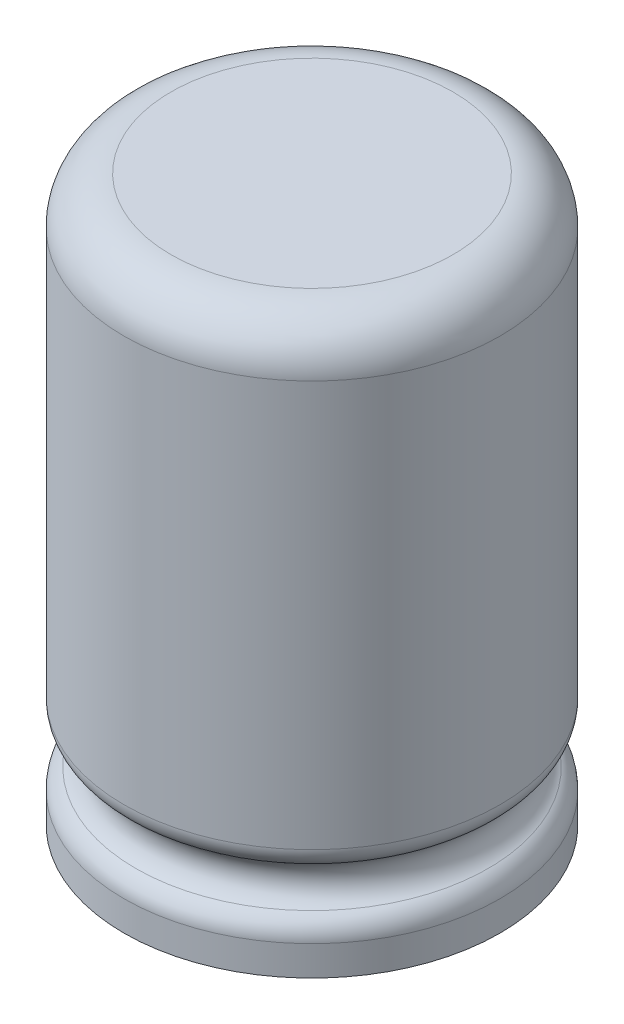
SolidWorks part; units mm, degrees
ref_plane "Front Plane" through (0, 0, 0) normal (0, 0, 1) x (1, 0, 0)
ref_plane "Top Plane" through (0, 0, 0) normal (0, 1, 0) x (1, 0, 0)
ref_plane "Right Plane" through (0, 0, 0) normal (1, 0, 0) x (0, 0, -1)
sketch "Sketch1" plane through (0, 0, 0) normal (0, 0, 1) x (1, 0, 0)
  line L0 (0, -5.1304) -> (0, 7.8969) construction
  line L1 (0, 0) -> (4, 0)
  line L2 (4, 0) -> (4, 1)
  line L3 (4, 2) -> (4, 11)
  line L4 (3, 12) -> (0, 12)
  line L5 (0, 0) -> (0, 12)
  arc A0 (4, 1) -> (4, 2) centre (4, 1.5) cw
  arc A1 (4, 11) -> (3, 12) centre (3, 11) ccw
  point P5 (4, 1.5)
  point P13 (4, 12)
  dimension "D5" = 1
  dimension "D1" = 4
  dimension "D2" = 1
  dimension "D3" = 0.5
  dimension "D4" = 12
revolve "Revolve1" add sketch "Sketch1" angle 360 about L0
fillet "Fillet1" radius 0.5 2 edges at (0, 2, -4) (0, 1, -4)
